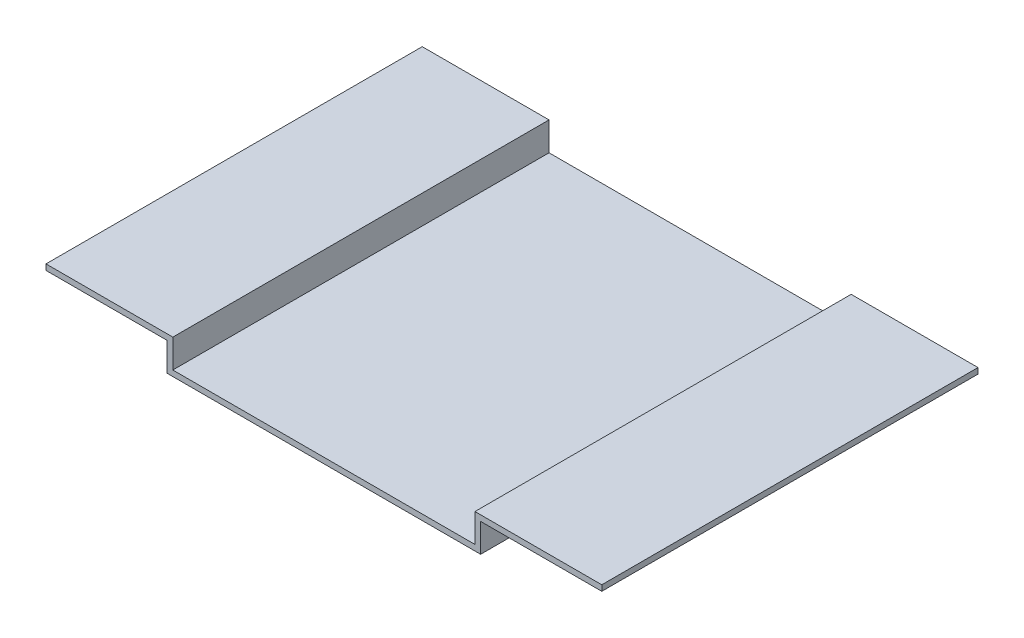
SolidWorks part; units mm, degrees
material "PVC 0.007 Plasticized"
ref_plane "Front Plane" through (0, 0, 0) normal (0, 0, 1) x (1, 0, 0)
ref_plane "Top Plane" through (0, 0, 0) normal (0, 1, 0) x (1, 0, 0)
ref_plane "Right Plane" through (0, 0, 0) normal (1, 0, 0) x (0, 0, -1)
sketch "Sketch1" plane through (0, 0, 0) normal (0, 0, 1) x (1, 0, 0)
  line L0 (-86.5918, -12.3214) -> (-42.0918, -12.3214)
  line L1 (-42.0918, -12.3214) -> (-42.0918, -22.3214)
  line L2 (-42.0918, -22.3214) -> (63.9082, -22.3214)
  line L3 (63.9082, -22.3214) -> (63.9082, -12.3214)
  line L4 (63.9082, -12.3214) -> (108.4082, -12.3214)
  line L5 (-86.5918, -14.3214) -> (-44.0918, -14.3214)
  line L6 (-44.0918, -14.3214) -> (-44.0918, -24.3214)
  line L7 (-44.0918, -24.3214) -> (65.9082, -24.3214)
  line L8 (65.9082, -24.3214) -> (65.9082, -14.3214)
  line L9 (65.9082, -14.3214) -> (108.4082, -14.3214)
  line L10 (-86.5918, -12.3214) -> (-86.5918, -14.3214)
  line L11 (108.4082, -12.3214) -> (108.4082, -14.3214)
  dimension "D1" = 195
  dimension "D2" = 110
  dimension "D3" = 10
  dimension "D4" = 10
  dimension "D6" = 42.5
  dimension "D5" = 2
extrude "Boss-Extrude1" add sketch "Sketch1" along normal blind 132
